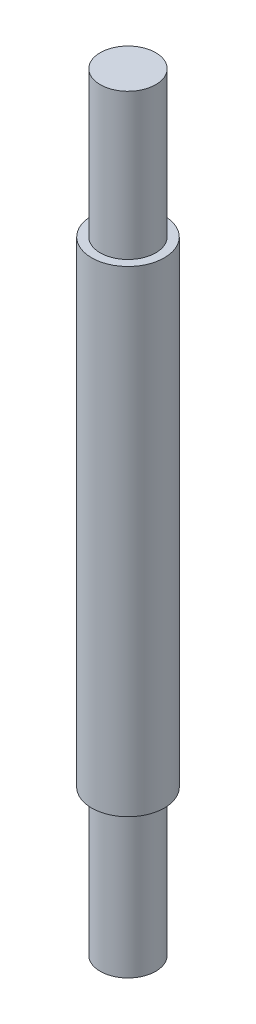
SolidWorks part; units mm, degrees
ref_plane "Front Plane" through (0, 0, 0) normal (0, 0, 1) x (1, 0, 0)
ref_plane "Top Plane" through (0, 0, 0) normal (0, 1, 0) x (1, 0, 0)
ref_plane "Right Plane" through (0, 0, 0) normal (1, 0, 0) x (0, 0, -1)
sketch "Sketch1" plane through (0, 0, 0) normal (0, 1, 0) x (1, 0, 0)
  circle A0 centre (0, 0) radius 0.095
  dimension "D1" = 0.19
extrude "Boss-Extrude1" add sketch "Sketch1" along normal mid plane 2.63
sketch "Sketch2" plane through (0, 0, 0) normal (0, 1, 0) x (1, 0, 0)
  circle A0 centre (0, 0) radius 0.1243
  circle A1 centre (0, 0) radius 0.095 construction
  circle A2 centre (0, 0) radius 0.095
  dimension "D1" = 0.2486
extrude "Boss-Extrude2" add sketch "Sketch2" along normal mid plane 1.632
